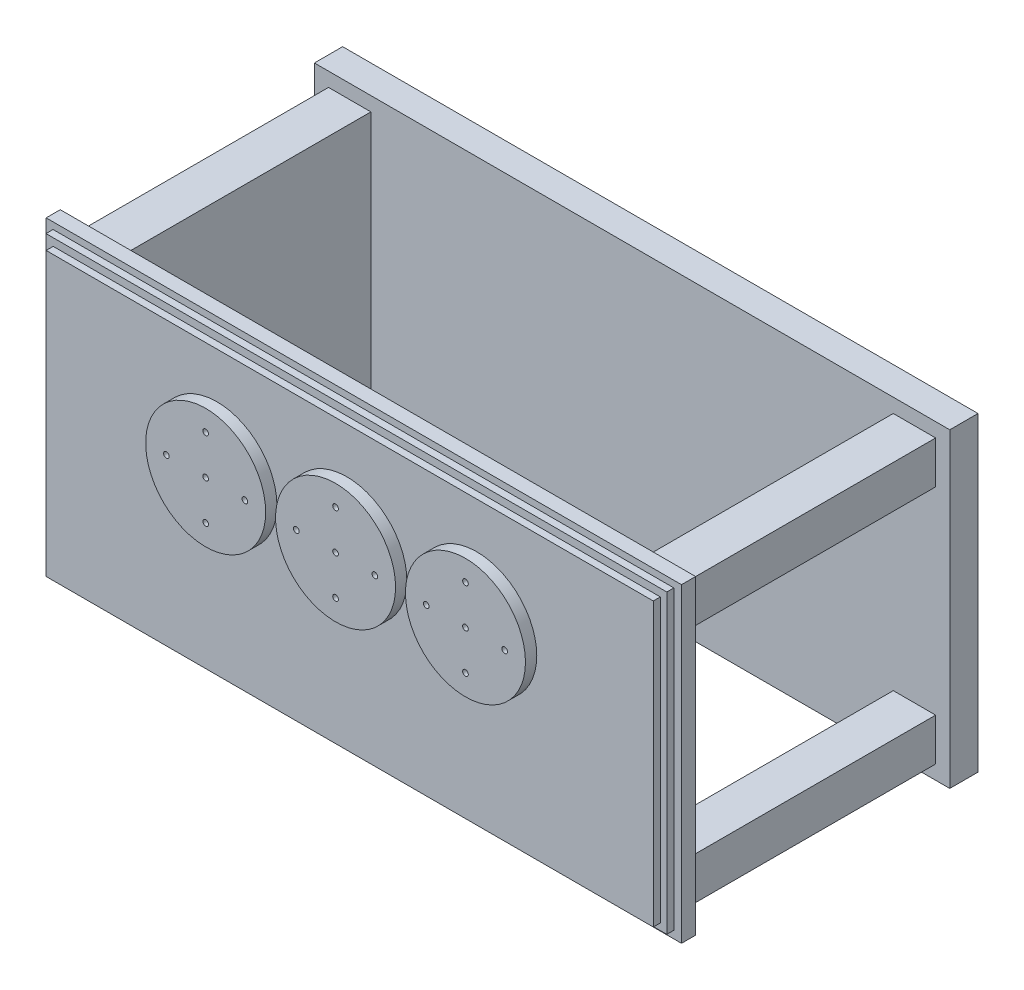
SolidWorks part; units mm, degrees
ref_plane "Front Plane" through (0, 0, 0) normal (0, 0, 1) x (1, 0, 0)
ref_plane "Top Plane" through (0, 0, 0) normal (0, 1, 0) x (1, 0, 0)
ref_plane "Right Plane" through (0, 0, 0) normal (1, 0, 0) x (0, 0, -1)
sketch "Sketch1" plane through (0, 0, 0) normal (0, 0, 1) x (1, 0, 0)
  line L1 (-225, 110) -> (225, 110)
  line L2 (-225, 110) -> (-225, -110)
  line L3 (-225, -110) -> (225, -110)
  line L4 (225, 110) -> (225, -110)
  line L5 (-225, 110) -> (225, -110) construction
  line L6 (-225, -110) -> (225, 110) construction
  point P0 (0, 0)
  dimension "D1" = 220
  dimension "D2" = 450
extrude "Boss-Extrude2" add sketch "Sketch1" along normal blind 20
sketch "Sketch4" plane through (0, 0, 20) normal (0, 0, 1) x (1, 0, 0)
  line L0 (-225, 110) -> (-225, -110) construction
  line L1 (0, -128.5158) -> (0, 129.1698) construction
  line L2 (-215, -70) -> (-185, -70)
  line L3 (-201.6724, 0) -> (213.2517, 0) construction
  line L4 (-215, -70) -> (-215, -100)
  line L5 (-215, -100) -> (-185, -100)
  line L6 (-185, -70) -> (-185, -100)
  line L7 (-215, -70) -> (-185, -100) construction
  line L8 (-215, -100) -> (-185, -70) construction
  line L9 (-225, -110) -> (225, -110) construction
  line L10 (215, -100) -> (185, -100)
  line L11 (185, -70) -> (185, -100)
  line L12 (215, -70) -> (185, -70)
  line L13 (215, -70) -> (215, -100)
  line L22 (215, 70) -> (215, 100)
  line L23 (215, 70) -> (185, 70)
  line L24 (185, 70) -> (185, 100)
  line L25 (215, 100) -> (185, 100)
  line L26 (-215, 100) -> (-185, 100)
  line L27 (-185, 70) -> (-185, 100)
  line L28 (-215, 70) -> (-185, 70)
  line L29 (-215, 70) -> (-215, 100)
  point P0 (-200, -85)
  dimension "D1" = 10
  dimension "D2" = 30
  dimension "D3" = 30
  dimension "D4" = 10
extrude "Boss-Extrude3" add sketch "Sketch4" along normal blind 200 and the other way blind 20
sketch3d "3DSketch1"
  line L0 (-225, 110, 200) -> (225, 110, 200)
  line L1 (225, 110, 200) -> (225, -110, 200)
  line L2 (225, -110, 200) -> (-225, -110, 200)
  line L3 (-225, -110, 200) -> (-225, 110, 200)
  dimension "D1" = 180
extrude "Boss-Extrude4" add sketch "3DSketch1" along direction (0, 0, 1) on the side of the normal blind 10 contours L0 L1 L2 L3
sketch "Sketch6" plane through (0, 0, 210) normal (0, 0, 1) x (1, 0, 0)
  line L0 (89.9029, 105.3082) -> (219.5837, 105.3082)
  line L5 (-220.0971, 105.3082) -> (89.9029, 105.3082)
  line L6 (219.5837, 105.3082) -> (219.5837, -104.6918)
  line L7 (-220.0971, 105.3082) -> (-220.0971, -104.6918)
  line L8 (219.5837, -104.6918) -> (89.9029, -104.6918)
  line L10 (-220.0971, -104.6918) -> (89.9029, -104.6918)
  point P0 (0, 0)
  dimension "D1" = 310
  dimension "D2" = 210
extrude "Boss-Extrude5" add sketch "Sketch6" along normal blind 5
sketch "Sketch9" plane through (0, 0, 220) normal (0, 0, 1) x (1, 0, 0)
  circle A0 centre (-94.0161, 25.18) radius 42.5
  circle A3 centre (-2.0161, 25.18) radius 42.5
  circle A4 centre (89.9839, 25.18) radius 42.5
  dimension "D1" = 85
  dimension "D2" = 3
extrude "Boss-Extrude7" add sketch "Sketch9" along normal blind 8
sketch "Sketch14" plane through (-215, 0, 0) normal (-1, 0, 0) x (0, 0, 1)
  line L0 (20, 100) -> (20, -100)
  line L1 (200, 100) -> (20, 100)
  line L2 (200, 100) -> (200, -100)
  line L3 (200, -100) -> (20, -100)
extrude "Boss-Extrude9" add sketch "Sketch14" against normal blind 30
sketch "Sketch15" plane through (0, 0, 228) normal (0, 0, 1) x (1, 0, 0)
  circle A0 centre (-94.0161, 52.976) radius 2
  circle A1 centre (-66.22, 25.18) radius 2
  circle A2 centre (-94.0161, -2.6161) radius 2
  circle A3 centre (-121.8122, 25.18) radius 2
  circle A4 centre (-2.0161, 52.976) radius 2
  circle A5 centre (-29.8122, 25.18) radius 2
  circle A6 centre (-2.0161, -2.6161) radius 2
  circle A7 centre (25.78, 25.18) radius 2
  circle A8 centre (89.9839, 52.976) radius 2
  circle A9 centre (62.1878, 25.18) radius 2
  circle A10 centre (89.9839, -2.6161) radius 2
  circle A11 centre (117.78, 25.18) radius 2
  circle A12 centre (-94.0161, 25.18) radius 2
  circle A13 centre (-2.0161, 25.18) radius 2
  circle A14 centre (89.9839, 25.18) radius 2
  point P12 (-94.0161, 25.18)
  dimension "D1" = 4
  dimension "D2" = 3
  dimension "D3" = 4
sketch "Sketch16" plane through (0, 0, 215) normal (0, 0, 1) x (1, 0, 0)
  line L0 (-215, 100) -> (215, 100)
  line L1 (215, 100) -> (215, -100)
  line L2 (215, -100) -> (-215, -100)
  line L3 (-215, -100) -> (-215, 100)
extrude "Boss-Extrude10" add sketch "Sketch16" along normal blind 5
extrude "Cut-Extrude2" cut sketch "Sketch15" against normal blind 125
